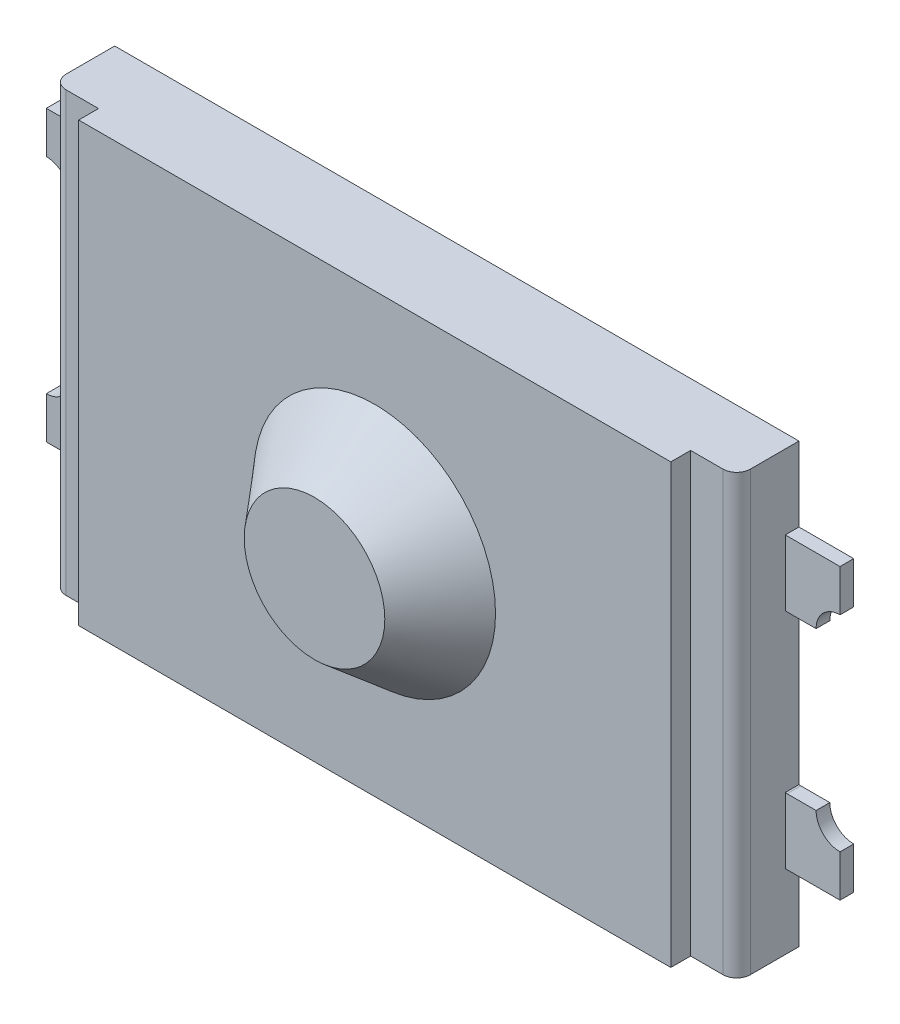
SolidWorks part; units mm, degrees
ref_plane "Front Plane" through (0, 0, 0) normal (0, 0, 1) x (1, 0, 0)
ref_plane "Top Plane" through (0, 0, 0) normal (0, 1, 0) x (1, 0, 0)
ref_plane "Right Plane" through (0, 0, 0) normal (1, 0, 0) x (0, 0, -1)
sketch "Sketch1" plane through (0, 0, 0) normal (0, 0, 1) x (1, 0, 0)
  line L1 (-1, -0.75) -> (1, -0.75)
  line L2 (-1, -0.75) -> (-1, 0.75)
  line L3 (-1, 0.75) -> (1, 0.75)
  line L4 (1, -0.75) -> (1, 0.75)
  line L5 (-1, -0.75) -> (1, 0.75) construction
  line L6 (-1, 0.75) -> (1, -0.75) construction
  point P0 (0, 0)
  dimension "D1" = 2
  dimension "D2" = 1.5
extrude "Boss-Extrude1" add sketch "Sketch1" along normal blind 0.03
sketch "Sketch2" plane through (0, 0, 0.03) normal (0, 0, 1) x (1, 0, 0)
  line L0 (-0.8106, 0.5784) -> (-0.8106, -0.5784)
  line L1 (-0.8106, -0.5784) -> (-1.0895, -0.5784)
  line L2 (-1.0895, -0.5784) -> (-1.0895, -0.528)
  line L3 (-1.0895, -0.528) -> (-1.45, -0.528)
  line L4 (-1.45, -0.528) -> (-1.45, -0.375)
  line L6 (-1.3626, -0.2876) -> (-1.2566, -0.2876)
  line L7 (-1.2066, -0.2376) -> (-1.2066, 0.2376)
  line L8 (-1.2066, 0) -> (-0.8106, 0) construction
  line L9 (-1.3626, 0.2876) -> (-1.2566, 0.2876)
  line L10 (-1.45, 0.528) -> (-1.45, 0.375)
  line L11 (-1.0895, 0.528) -> (-1.45, 0.528)
  line L12 (-1.0895, 0.5784) -> (-1.0895, 0.528)
  line L13 (-0.8106, 0.5784) -> (-1.0895, 0.5784)
  arc A1 (-1.45, -0.375) -> (-1.3626, -0.2876) centre (-1.45, -0.2876) ccw
  arc A2 (-1.2566, -0.2876) -> (-1.2066, -0.2376) centre (-1.2566, -0.2376) ccw
  arc A3 (-1.2566, 0.2876) -> (-1.2066, 0.2376) centre (-1.2566, 0.2376) cw
  arc A4 (-1.45, 0.375) -> (-1.3626, 0.2876) centre (-1.45, 0.2876) cw
  dimension "D2" = 0.05
  dimension "D1" = 0.375
  dimension "D3" = 1.45
extrude "Boss-Extrude2" add sketch "Sketch2" along normal blind 0.05
mirror "Mirror1" about plane through (0, 0, 0) normal (1, 0, 0) of "Boss-Extrude2"
sketch "Sketch3" plane through (0, 0, 0) normal (0, 1, 0) x (1, 0, 0)
  line L0 (0, -0.03) -> (0, -0.33) construction
  line L1 (1, -0.03) -> (-1, -0.03) construction
  line L2 (1.0817, -0.33) -> (-1.0817, -0.33)
  line L3 (-1.0817, -0.33) -> (-1.0817, -0.2575)
  line L4 (-1.0817, -0.2575) -> (-1.2, -0.2575)
  line L5 (-1.25, -0.2075) -> (-1.25, -0.03)
  line L6 (-1.0895, -0.03) -> (-1.45, -0.03) construction
  line L7 (-1.25, -0.03) -> (1.25, -0.03)
  line L8 (1.25, -0.2075) -> (1.25, -0.03)
  line L9 (1.0817, -0.2575) -> (1.2, -0.2575)
  line L10 (1.0817, -0.33) -> (1.0817, -0.2575)
  arc A0 (-1.2, -0.2575) -> (-1.25, -0.2075) centre (-1.2, -0.2075) cw
  arc A1 (1.2, -0.2575) -> (1.25, -0.2075) centre (1.2, -0.2075) ccw
  dimension "D3" = 0.05
  dimension "D1" = 1.25
  dimension "D2" = 0.3
extrude "Boss-Extrude3" add sketch "Sketch3" along normal blind 0.8 and the other way blind 0.8 separate body
sketch "Sketch4" plane through (0, 0, 0.33) normal (0, 0, 1) x (1, 0, 0)
  circle A0 centre (0, 0) radius 0.4414
extrude "Boss-Extrude5" add sketch "Sketch4" along direction (0, 0, 1) on the side of the normal offset from surface 0.55 draft 40 contours A0
